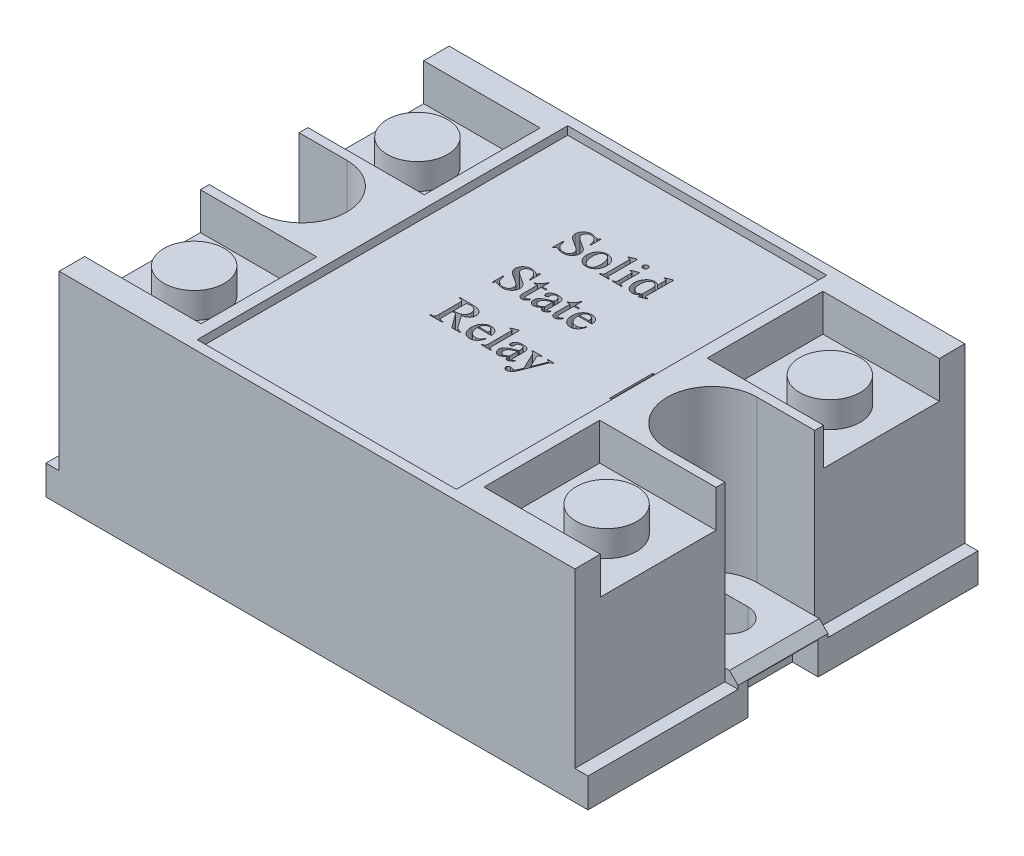
SolidWorks part; units mm, degrees
ref_plane "Front Plane" through (0, 0, 0) normal (0, 0, 1) x (1, 0, 0)
ref_plane "Top Plane" through (0, 0, 0) normal (0, 1, 0) x (1, 0, 0)
ref_plane "Right Plane" through (0, 0, 0) normal (1, 0, 0) x (0, 0, -1)
sketch "Sketch1" plane through (0, 0, 0) normal (0, 1, 0) x (1, 0, 0)
  line L1 (-31.375, -22.575) -> (31.375, -22.575)
  line L2 (-31.375, -22.575) -> (-31.375, 22.575)
  line L3 (-31.375, 22.575) -> (31.375, 22.575)
  line L4 (31.375, -22.575) -> (31.375, 22.575)
  line L5 (-31.375, -22.575) -> (31.375, 22.575) construction
  line L6 (-31.375, 22.575) -> (31.375, -22.575) construction
  point P0 (0, 0)
  dimension "D1" = 62.75
  dimension "D2" = 45.15
extrude "Boss-Extrude1" add sketch "Sketch1" along normal blind 23.4
sketch "Sketch2" plane through (0, 23.4, 0) normal (0, 1, 0) x (1, 0, 0)
  line L1 (-15, -21.45) -> (15, -21.45)
  line L2 (-15, -21.45) -> (-15, 21.45)
  line L3 (-15, 21.45) -> (15, 21.45)
  line L4 (15, -21.45) -> (15, 21.45)
  line L5 (-15, -21.45) -> (15, 21.45) construction
  line L6 (-15, 21.45) -> (15, -21.45) construction
  point P0 (0, 0)
  dimension "D1" = 30
  dimension "D2" = 42.9
extrude "Cut-Extrude1" cut sketch "Sketch2" against normal blind 0.95
sketch "Sketch3" plane through (0, 23.4, 0) normal (0, 1, 0) x (1, 0, 0)
  line L0 (-31.375, 22.575) -> (-31.375, -22.575) construction
  line L1 (-31.375, 19.625) -> (-16.375, 19.625)
  line L2 (-31.375, 19.625) -> (-31.375, 6.225)
  line L3 (-31.375, 6.225) -> (-16.375, 6.225)
  line L4 (-16.375, 19.625) -> (-16.375, 6.225)
  line L5 (-31.375, 0) -> (31.375, 0) construction
  line L6 (31.375, -22.575) -> (31.375, 22.575) construction
  line L7 (0, 22.575) -> (0, -22.575) construction
  line L8 (31.375, 22.575) -> (-31.375, 22.575) construction
  line L9 (-31.375, -22.575) -> (31.375, -22.575) construction
  line L10 (-16.375, -19.625) -> (-16.375, -6.225)
  line L11 (-31.375, -6.225) -> (-16.375, -6.225)
  line L12 (-31.375, -19.625) -> (-31.375, -6.225)
  line L13 (-31.375, -19.625) -> (-16.375, -19.625)
  line L14 (31.375, -19.625) -> (16.375, -19.625)
  line L15 (31.375, -19.625) -> (31.375, -6.225)
  line L16 (31.375, -6.225) -> (16.375, -6.225)
  line L17 (16.375, -19.625) -> (16.375, -6.225)
  line L18 (16.375, 19.625) -> (16.375, 6.225)
  line L19 (31.375, 6.225) -> (16.375, 6.225)
  line L20 (31.375, 19.625) -> (31.375, 6.225)
  line L21 (31.375, 19.625) -> (16.375, 19.625)
  dimension "D1" = 13.4
  dimension "D2" = 2.95
  dimension "D3" = 15
extrude "Cut-Extrude2" cut sketch "Sketch3" against normal blind 4.3
sketch "Sketch4" plane through (0, 19.1, 0) normal (0, 1, 0) x (1, 0, 0)
  line L0 (-23.875, 19.625) -> (-23.875, 6.225) construction
  line L1 (-16.375, 19.625) -> (-31.375, 19.625) construction
  line L2 (-31.375, 6.225) -> (-16.375, 6.225) construction
  line L3 (0, 22.575) -> (0, -22.575) construction
  line L4 (31.375, 22.575) -> (-31.375, 22.575) construction
  line L5 (-31.375, -22.575) -> (31.375, -22.575) construction
  line L6 (-31.375, 0) -> (31.375, 0) construction
  line L7 (-31.375, 6.225) -> (-31.375, -6.225) construction
  line L8 (31.375, -6.225) -> (31.375, 6.225) construction
  line L9 (-23.875, -19.625) -> (-23.875, -6.225) construction
  line L10 (23.875, -19.625) -> (23.875, -6.225) construction
  line L11 (23.875, 19.625) -> (23.875, 6.225) construction
  circle A0 centre (-23.875, 12.925) radius 3.5
  circle A1 centre (-23.875, -12.925) radius 3.5
  circle A2 centre (23.875, -12.925) radius 3.5
  circle A3 centre (23.875, 12.925) radius 3.5
  dimension "D1" = 7
extrude "Boss-Extrude2" add sketch "Sketch4" along normal blind 3
sketch "Sketch5" plane through (0, 23.4, 0) normal (0, 1, 0) x (1, 0, 0)
  line L0 (-31.375, 0) -> (-24.325, 0) construction
  line L3 (31.375, 0) -> (23.175, 0) construction
  line L4 (31.375, -6.225) -> (31.375, 6.225) construction
  line L5 (31.375, -5.2) -> (23.175, -5.2)
  line L6 (31.375, 5.2) -> (23.175, 5.2)
  line L7 (-31.375, 6.225) -> (-31.375, -6.225) construction
  line L8 (-31.375, 5.2) -> (-24.325, 5.2)
  line L9 (-31.375, -5.2) -> (-24.325, -5.2)
  arc A0 (31.375, -5.2) -> (31.375, 5.2) centre (31.375, 0) ccw
  arc A1 (23.175, 5.2) -> (23.175, -5.2) centre (23.175, 0) ccw
  arc A2 (-31.375, 5.2) -> (-31.375, -5.2) centre (-31.375, 0) ccw
  arc A3 (-24.325, -5.2) -> (-24.325, 5.2) centre (-24.325, 0) ccw
  point P4 (-27.85, 0)
  point P11 (27.275, 0)
  dimension "D1" = 10.4
  dimension "D2" = 13.4
  dimension "D3" = 12.25
extrude "Cut-Extrude3" cut sketch "Sketch5" against normal blind 18.6
sketch "Sketch6" plane through (0, 22.45, 0) normal (0, 1, 0) x (1, 0, 0)
  line L0 (31.375, 0) -> (0, 0) construction
  line L1 (31.375, -5.2) -> (31.375, 5.2) construction
  line L2 (14, 2.5) -> (14, -2.5)
  line L3 (15, -21.45) -> (15, 21.45) construction
  dimension "D1" = 1
  dimension "D2" = 5
extrude "Cut-Extrude-Thin1" cut sketch "Sketch6" against normal blind 1 and the other way through all thin
sketch "Sketch7" plane through (0, 4.8, 0) normal (0, 1, 0) x (1, 0, 0)
  line L0 (22.275, 0) -> (25.075, 0) construction
  line L1 (22.275, 2.25) -> (25.075, 2.25)
  line L2 (22.275, -2.25) -> (25.075, -2.25)
  line L3 (31.375, -5.2) -> (31.375, 5.2) construction
  arc A0 (22.275, 2.25) -> (22.275, -2.25) centre (22.275, 0) ccw
  arc A1 (25.075, -2.25) -> (25.075, 2.25) centre (25.075, 0) ccw
  point P3 (23.675, 0)
  dimension "D3" = 7.3
  dimension "D1" = 4.05
  dimension "D2" = 4.5
extrude "Cut-Extrude4" cut sketch "Sketch7" against normal through all
sketch "Sketch8" plane through (0, 4.8, 0) normal (0, 1, 0) x (1, 0, 0)
  line L0 (22.275, 0) -> (-31.375, 0) construction
  line L1 (-31.375, 5.2) -> (-31.375, -5.2) construction
  circle A0 centre (-23.825, 0) radius 2.25
  arc A3 (-24.325, -5.2) -> (-24.325, 5.2) centre (-24.325, 0) ccw construction
  dimension "D1" = 4.5
  dimension "D2" = 5.7
extrude "Cut-Extrude5" cut sketch "Sketch8" against normal through all
sketch "Sketch9" plane through (0, 23.4, 0) normal (0, 1, 0) x (1, 0, 0)
  line L0 (-31.375, -22.575) -> (31.375, -22.575) construction
  line L1 (-31.375, 22.575) -> (-29.85, 22.575)
  line L2 (-31.375, 22.575) -> (-31.375, -22.575)
  line L3 (-31.375, -22.575) -> (-29.85, -22.575)
  line L4 (-29.85, 22.575) -> (-29.85, -22.575)
  line L5 (0, 22.575) -> (0, -22.575) construction
  line L6 (31.375, 22.575) -> (-31.375, 22.575) construction
  line L7 (29.85, 22.575) -> (29.85, -22.575)
  line L8 (31.375, -22.575) -> (29.85, -22.575)
  line L9 (31.375, 22.575) -> (31.375, -22.575)
  line L10 (31.375, 22.575) -> (29.85, 22.575)
  dimension "D1" = 59.7
extrude "Cut-Extrude6" cut sketch "Sketch9" against normal blind 20
sketch "Sketch11" plane through (0, 3.4, 0) normal (0, 1, 0) x (1, 0, 0)
  line L0 (-31.375, 22.575) -> (-31.375, -22.575) construction
  line L1 (-29.85, 5.2) -> (-31.375, 5.2)
  line L2 (-29.85, 5.2) -> (-29.85, -5.2)
  line L3 (-29.85, -5.2) -> (-31.375, -5.2)
  line L4 (-31.375, 5.2) -> (-31.375, -5.2)
  line L5 (31.375, -22.575) -> (31.375, 22.575) construction
  line L6 (29.85, 5.2) -> (31.375, 5.2)
  line L7 (29.85, 5.2) -> (29.85, -5.2)
  line L8 (29.85, -5.2) -> (31.375, -5.2)
  line L9 (31.375, 5.2) -> (31.375, -5.2)
  line L10 (29.85, 22.575) -> (29.85, -22.575) construction
extrude "Boss-Extrude3" add sketch "Sketch11" along normal up to surface (1.4 mm away) up to face at (-25.7875, 4.8, 0)
chamfer "Chamfer1" distance 1 angle 45 2 edges at (31.375, 4.8, 0) (-31.375, 4.8, 0)
sketch "Sketch10" plane through (0, 0, 0) normal (0, -1, 0) x (1, 0, 0)
  line L0 (0, 22.575) -> (0, -22.575) construction
  line L1 (-31.375, 22.575) -> (31.375, 22.575) construction
  line L2 (31.375, -22.575) -> (-31.375, -22.575) construction
  line L3 (-31.375, 0) -> (31.375, 0) construction
  line L4 (-31.375, -22.575) -> (-31.375, 22.575) construction
  line L5 (31.375, 22.575) -> (31.375, -22.575) construction
  line L6 (-28.375, 4.075) -> (-31.375, -4.075) construction
  line L7 (28.375, -4.075) -> (31.375, -4.075)
  line L8 (28.375, -4.075) -> (28.375, 4.075)
  line L9 (28.375, 4.075) -> (31.375, 4.075)
  line L10 (31.375, -4.075) -> (31.375, 4.075)
  line L11 (28.375, -4.075) -> (31.375, 4.075) construction
  line L12 (28.375, 4.075) -> (31.375, -4.075) construction
  line L13 (-28.375, -4.075) -> (-31.375, 4.075) construction
  line L14 (-31.375, -4.075) -> (-31.375, 4.075)
  line L15 (-28.375, 4.075) -> (-31.375, 4.075)
  line L16 (-28.375, -4.075) -> (-28.375, 4.075)
  line L17 (-28.375, -4.075) -> (-31.375, -4.075)
  point P12 (29.875, 0)
  point P21 (-29.875, 0)
  dimension "D1" = 8.15
  dimension "D2" = 3
extrude "Cut-Extrude7" cut sketch "Sketch10" against normal blind 3.75
sketch "Sketch13" plane through (0, 22.45, 0) normal (0, 1, 0) x (1, 0, 0)
sketch "Sketch14" plane through (0, 22.45, 0) normal (0, 1, 0) x (1, 0, 0)
  text T0 "Solid\r\nState \r\nRelay" font "Times New Roman" height 3.5
extrude "Cut-Extrude8" cut sketch "Sketch14" against normal blind 5
